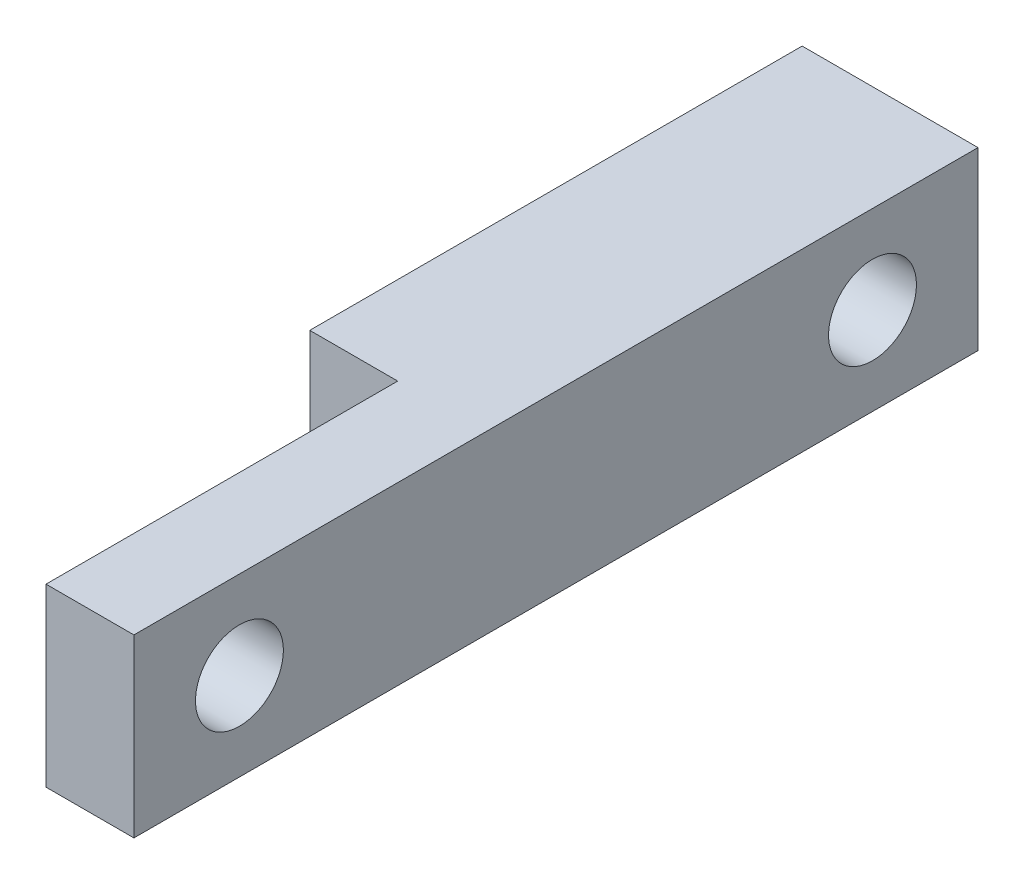
SolidWorks part; units mm, degrees
ref_plane "Front Plane" through (0, 0, 0) normal (0, 0, 1) x (1, 0, 0)
ref_plane "Top Plane" through (0, 0, 0) normal (0, 1, 0) x (1, 0, 0)
ref_plane "Right Plane" through (0, 0, 0) normal (1, 0, 0) x (0, 0, -1)
sketch "Sketch1" plane through (0, 0, 0) normal (1, 0, 0) x (0, 0, -1)
  line L1 (0, 0) -> (30.48, 0)
  line L2 (0, 0) -> (0, 6.35)
  line L3 (0, 6.35) -> (30.48, 6.35)
  line L4 (30.48, 0) -> (30.48, 6.35)
  dimension "D1" = 6.35
  dimension "D2" = 30.48
extrude "Boss-Extrude1" add sketch "Sketch1" along normal blind 6.35
hole_wizard "1/8 (0.125) Diameter Hole1" positions "Sketch3" profile "Sketch2" hole size "1/8" standard "ANSI Inch"
sketch "Sketch3" plane through (6.35, 0, 0) normal (1, 0, 0) x (0, 0, -1)
  line L0 (0, 6.35) -> (0, 0) construction
  line L1 (0, 6.35) -> (0, 0) construction
  point P0 (3.81, 3.175)
  point P7 (0, 3.175)
  dimension "D1" = 0
  dimension "D2" = 3.81
sketch "Sketch2" plane through (6.35, 3.175, -3.81) normal (0, 1, 0) x (0, 0, -1)
  line L0 (0, 0) -> (0, 71.0579)
  line L1 (0, 71.0579) -> (1.5875, 70.104)
  line L2 (1.5875, 70.104) -> (1.5875, 0)
  line L5 (1.5875, 0) -> (0, 0)
  line L10 (0, 71.0579) -> (-1.5875, 70.104) construction
  line L11 (0, -6.35) -> (0, 107.95) construction
  dimension "Hole Dia." = 3.175
  dimension "Hole Depth" = 70.104
  dimension "Drill Angle" = 118
sketch "Sketch4" plane through (0, 0, 0) normal (-1, 0, 0) x (0, 0, 1)
  line L0 (0, 0) -> (-30.48, 0) construction
  line L1 (0, 6.35) -> (-12.7, 6.35)
  line L2 (0, 6.35) -> (0, 0)
  line L3 (0, 0) -> (-12.7, 0)
  line L4 (-12.7, 6.35) -> (-12.7, 0)
  dimension "D1" = 12.7
extrude "Cut-Extrude1" cut sketch "Sketch4" against normal blind 3.175
hole_wizard "1/8 (0.125) Diameter Hole2" positions "Sketch6" profile "Sketch5" hole size "1/8" standard "ANSI Inch"
sketch "Sketch6" plane through (6.35, 0, 0) normal (1, 0, 0) x (0, 0, -1)
  line L0 (30.48, 0) -> (30.48, 6.35) construction
  point P0 (26.67, 3.175)
  point P2 (33.02, 3.175)
  point P7 (30.48, 3.175)
  dimension "D1" = 3.81
  dimension "D2" = 6.35
  dimension "D3" = 0
sketch "Sketch5" plane through (6.35, 3.175, -26.67) normal (0, 1, 0) x (0, 0, -1)
  line L0 (0, 0) -> (0, 71.0579)
  line L1 (0, 71.0579) -> (1.5875, 70.104)
  line L2 (1.5875, 70.104) -> (1.5875, 0)
  line L5 (1.5875, 0) -> (0, 0)
  line L10 (0, 71.0579) -> (-1.5875, 70.104) construction
  line L11 (0, -6.35) -> (0, 107.95) construction
  dimension "Hole Dia." = 3.175
  dimension "Hole Depth" = 70.104
  dimension "Drill Angle" = 118
